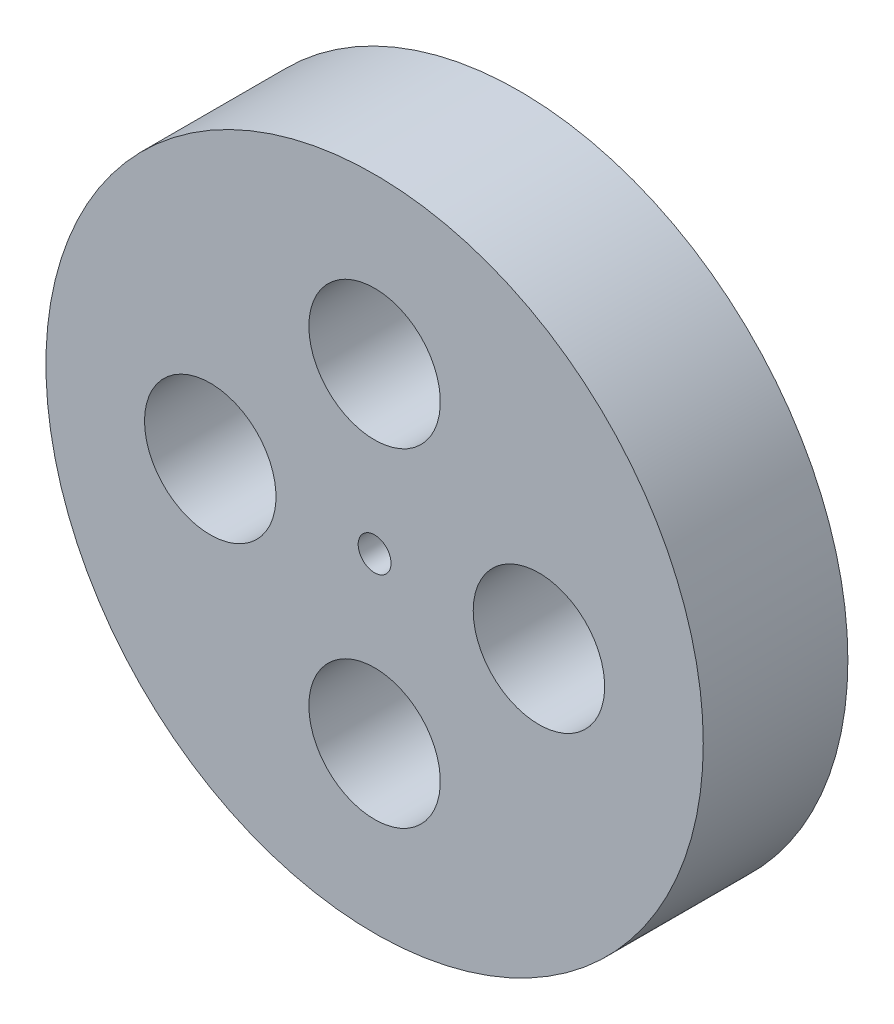
SolidWorks part; units mm, degrees
ref_plane "Plan de face" through (0, 0, 0) normal (0, 0, 1) x (1, 0, 0)
ref_plane "Plan de dessus" through (0, 0, 0) normal (0, 1, 0) x (1, 0, 0)
ref_plane "Plan de droite" through (0, 0, 0) normal (1, 0, 0) x (0, 0, -1)
sketch "Esquisse1" plane through (0, 0, 0) normal (0, 0, 1) x (1, 0, 0)
  circle A0 centre (0, 0) radius 50
extrude "Boss.-Extru.1" add sketch "Esquisse1" along normal blind 22
sketch "Esquisse2" plane through (0, 0, 22) normal (0, 0, 1) x (1, 0, 0)
  circle A0 centre (0, 0) radius 2.5
extrude "Enlèv. mat.-Extru.1" cut sketch "Esquisse2" against normal blind 7
sketch "Esquisse3" plane through (0, 0, 0) normal (0, 0, -1) x (-1, 0, 0)
  line L0 (-2.2495, 1.0907) -> (-2.3661, -0.8072)
  circle A0 centre (0, 0) radius 2.5
extrude "Enlèv. mat.-Extru.3" cut sketch "Esquisse3" against normal blind 15 contours L0 A0
sketch "Esquisse4" plane through (0, 0, 0) normal (0, 0, -1) x (-1, 0, 0)
  circle A0 centre (0, 25) radius 10
extrude "Enlèv. mat.-Extru.5" cut sketch "Esquisse4" against normal blind 22
sketch "Esquisse5" plane through (0, 0, 0) normal (0, 0, -1) x (-1, 0, 0)
  circle A0 centre (25, 0) radius 10
extrude "Enlèv. mat.-Extru.6" cut sketch "Esquisse5" against normal blind 22
sketch "Esquisse6" plane through (0, 0, 0) normal (0, 0, -1) x (-1, 0, 0)
  circle A0 centre (0, -25) radius 10
extrude "Enlèv. mat.-Extru.7" cut sketch "Esquisse6" against normal blind 22
sketch "Esquisse7" plane through (0, 0, 0) normal (0, 0, -1) x (-1, 0, 0)
  circle A0 centre (-25, 0) radius 10
extrude "Enlèv. mat.-Extru.8" cut sketch "Esquisse7" against normal blind 22
